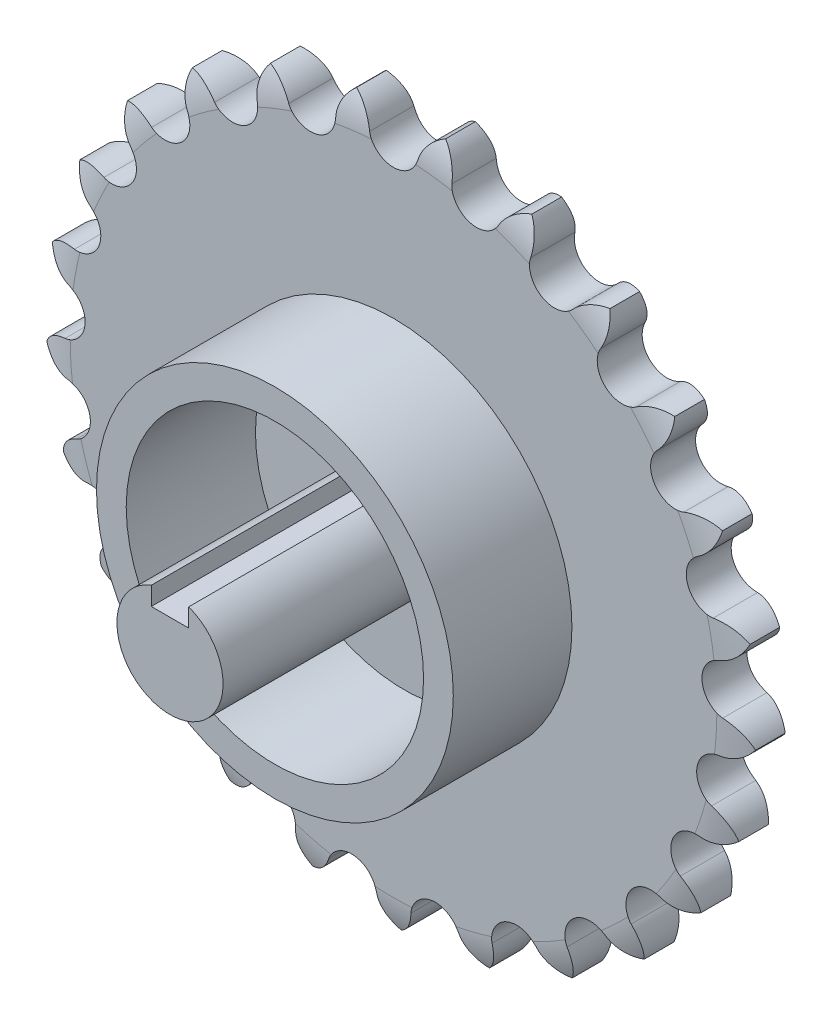
SolidWorks part; units mm, degrees
material "Acero aleado fundido"
ref_plane "Alzado" through (0, 0, 0) normal (0, 0, 1) x (1, 0, 0)
ref_plane "Planta" through (0, 0, 0) normal (0, 1, 0) x (1, 0, 0)
ref_plane "Vista lateral" through (0, 0, 0) normal (1, 0, 0) x (0, 0, -1)
sketch "Croquis1" plane through (0, 0, 0) normal (0, 0, 1) x (1, 0, 0)
  line L0 (0, 0) -> (0, 57) construction
  circle A0 centre (0, 0) radius 57 construction
  circle A1 centre (0, 0) radius 53.5 construction
  circle A2 centre (0, 0) radius 52 construction
  arc A5 (-3.8808, 52.5307) -> (3.8808, 52.5307) centre (0, 53.5) ccw
  arc A6 (7.3536, 56.5237) -> (3.8808, 52.5307) centre (9.537, 51.118) ccw
  arc A7 (15.1992, 49.7291) -> (15.3656, 51.246) centre (9.537, 51.118) ccw
  arc A8 (-7.3536, 56.5237) -> (-3.8808, 52.5307) centre (-9.537, 51.118) cw
  arc A9 (6.9343, 56.5766) -> (9.305, 51.8455) centre (3.4751, 51.8838) cw
  arc A10 (9.305, 51.8455) -> (16.8227, 49.9152) centre (13.3049, 51.8192) ccw
  arc A11 (21.1795, 52.9191) -> (16.8227, 49.9152) centre (21.9499, 47.1402) ccw
  arc A12 (20.7865, 53.0747) -> (21.9061, 47.9026) centre (16.2689, 49.3895) cw
  arc A13 (21.9061, 47.9026) -> (28.7076, 44.1634) centre (25.7738, 46.8824) ccw
  arc A14 (33.6745, 45.9894) -> (28.7076, 44.1634) centre (32.9836, 40.2005) ccw
  arc A15 (33.3325, 46.2379) -> (33.1308, 40.9498) centre (28.0405, 43.7919) cw
  arc A16 (33.1308, 40.9498) -> (38.7887, 35.6367) centre (36.6233, 38.9998) ccw
  arc A17 (44.0537, 36.1701) -> (38.7887, 35.6367) centre (41.9448, 30.7348) ccw
  arc A18 (43.7842, 36.4958) -> (42.2737, 31.424) centre (38.0501, 35.4427) cw
  arc A19 (42.2737, 31.424) -> (46.4326, 24.8707) centre (45.1715, 28.6667) ccw
  arc A20 (51.6648, 24.078) -> (46.4326, 24.8707) centre (48.2705, 19.338) ccw
  arc A21 (51.4848, 24.4605) -> (48.7604, 19.9237) centre (45.669, 24.8666) cw
  arc A22 (48.7604, 19.9237) -> (51.1589, 12.542) centre (50.8815, 16.5324) ccw
  arc A23 (56.0296, 10.4731) -> (51.1589, 12.542) centre (51.5632, 6.7261) ccw
  arc A24 (55.9504, 10.8883) -> (52.1834, 7.1716) centre (50.4183, 12.7279) cw
  arc A25 (52.1834, 7.1716) -> (52.6707, -0.5747) centre (53.3944, 3.3593) ccw
  arc A26 (56.8739, -3.79) -> (52.6707, -0.5747) centre (51.6159, -6.3085) ccw
  arc A27 (56.9004, -3.3681) -> (52.3274, -6.0312) centre (51.9996, -0.2105) cw
  arc A28 (52.3274, -6.0312) -> (50.8731, -13.6553) centre (52.5524, -10.0249) ccw
  arc A29 (54.1445, -17.8148) -> (50.8731, -13.6553) centre (48.4255, -18.9466) ccw
  arc A30 (54.2752, -17.4128) -> (49.1836, -18.855) centre (50.3136, -13.1356) cw
  arc A31 (49.1836, -18.855) -> (45.8788, -25.8779) centre (48.4082, -22.7792) ccw
  arc A32 (48.0131, -30.7204) -> (45.8788, -25.8779) centre (42.1922, -30.3943) ccw
  arc A33 (48.2396, -30.3635) -> (42.9493, -30.4941) centre (45.4662, -25.2354) cw
  arc A34 (42.9493, -30.4941) -> (38.0019, -36.4745) centre (41.2225, -34.1022) ccw
  arc A35 (38.8649, -41.6956) -> (38.0019, -36.4745) centre (33.3079, -39.9322) ccw
  arc A36 (39.173, -41.4063) -> (34.0164, -40.2172) centre (37.762, -35.7496) cw
  arc A37 (34.0164, -40.2172) -> (27.7372, -44.7793) centre (31.4465, -43.2824) ccw
  arc A38 (27.2746, -50.051) -> (27.7372, -44.7793) centre (22.3308, -46.961) ccw
  arc A39 (27.645, -49.8473) -> (22.9461, -47.4132) centre (27.6851, -44.0175) cw
  arc A40 (22.9461, -47.4132) -> (15.7296, -50.2704) centre (19.6947, -49.743) ccw
  arc A41 (13.9705, -55.2614) -> (15.7296, -50.2704) centre (9.9505, -51.0391) ccw
  arc A42 (14.3799, -55.1563) -> (10.434, -51.6301) centre (15.8686, -49.5196) cw
  arc A43 (10.434, -51.6301) -> (2.7337, -52.6029) centre (6.7053, -53.0781) ccw
  arc A44 (-0.2113, -56.9996) -> (2.7337, -52.6029) centre (-3.055, -51.9102) ccw
  arc A45 (0.2113, -56.9996) -> (-2.7337, -52.6029) centre (3.055, -51.9102) cw
  arc A46 (-2.7337, -52.6029) -> (-10.434, -51.6301) centre (-6.7053, -53.0781) ccw
  arc A47 (-14.3799, -55.1563) -> (-10.434, -51.6301) centre (-15.8686, -49.5196) ccw
  arc A48 (-13.9705, -55.2614) -> (-15.7296, -50.2704) centre (-9.9505, -51.0391) cw
  arc A49 (-15.7296, -50.2704) -> (-22.9461, -47.4132) centre (-19.6947, -49.743) ccw
  arc A50 (-27.645, -49.8473) -> (-22.9461, -47.4132) centre (-27.6851, -44.0175) ccw
  arc A51 (-27.2746, -50.051) -> (-27.7372, -44.7793) centre (-22.3308, -46.961) cw
  arc A52 (-27.7372, -44.7793) -> (-34.0164, -40.2172) centre (-31.4465, -43.2824) ccw
  arc A53 (-39.173, -41.4063) -> (-34.0164, -40.2172) centre (-37.762, -35.7496) ccw
  arc A54 (-38.8649, -41.6956) -> (-38.0019, -36.4745) centre (-33.3079, -39.9322) cw
  arc A55 (-38.0019, -36.4745) -> (-42.9493, -30.4941) centre (-41.2225, -34.1022) ccw
  arc A56 (-48.2396, -30.3635) -> (-42.9493, -30.4941) centre (-45.4662, -25.2354) ccw
  arc A57 (-48.0131, -30.7204) -> (-45.8788, -25.8779) centre (-42.1922, -30.3943) cw
  arc A58 (-45.8788, -25.8779) -> (-49.1836, -18.855) centre (-48.4082, -22.7792) ccw
  arc A59 (-54.2752, -17.4128) -> (-49.1836, -18.855) centre (-50.3136, -13.1356) ccw
  arc A60 (-54.1445, -17.8148) -> (-50.8731, -13.6553) centre (-48.4255, -18.9466) cw
  arc A61 (-50.8731, -13.6553) -> (-52.3274, -6.0312) centre (-52.5524, -10.0249) ccw
  arc A62 (-56.9004, -3.3681) -> (-52.3274, -6.0312) centre (-51.9996, -0.2105) ccw
  arc A63 (-56.8739, -3.79) -> (-52.6707, -0.5747) centre (-51.6159, -6.3085) cw
  arc A64 (-52.6707, -0.5747) -> (-52.1834, 7.1716) centre (-53.3944, 3.3593) ccw
  arc A65 (-55.9504, 10.8883) -> (-52.1834, 7.1716) centre (-50.4183, 12.7279) ccw
  arc A66 (-56.0296, 10.4731) -> (-51.1589, 12.542) centre (-51.5632, 6.7261) cw
  arc A67 (-51.1589, 12.542) -> (-48.7604, 19.9237) centre (-50.8815, 16.5324) ccw
  arc A68 (-51.4848, 24.4605) -> (-48.7604, 19.9237) centre (-45.669, 24.8666) ccw
  arc A69 (-51.6648, 24.078) -> (-46.4326, 24.8707) centre (-48.2705, 19.338) cw
  arc A70 (-46.4326, 24.8707) -> (-42.2737, 31.424) centre (-45.1715, 28.6667) ccw
  arc A71 (-43.7842, 36.4958) -> (-42.2737, 31.424) centre (-38.0501, 35.4427) ccw
  arc A72 (-44.0537, 36.1701) -> (-38.7887, 35.6367) centre (-41.9448, 30.7348) cw
  arc A73 (-38.7887, 35.6367) -> (-33.1308, 40.9498) centre (-36.6233, 38.9998) ccw
  arc A74 (-33.3325, 46.2379) -> (-33.1308, 40.9498) centre (-28.0405, 43.7919) ccw
  arc A75 (-33.6745, 45.9894) -> (-28.7076, 44.1634) centre (-32.9836, 40.2005) cw
  arc A76 (-28.7076, 44.1634) -> (-21.9061, 47.9026) centre (-25.7738, 46.8824) ccw
  arc A77 (-20.7865, 53.0747) -> (-21.9061, 47.9026) centre (-16.2689, 49.3895) ccw
  arc A78 (-21.1795, 52.9191) -> (-16.8227, 49.9152) centre (-21.9499, 47.1402) cw
  arc A79 (-16.8227, 49.9152) -> (-9.305, 51.8455) centre (-13.3049, 51.8192) ccw
  arc A80 (-6.9343, 56.5766) -> (-9.305, 51.8455) centre (-3.4751, 51.8838) ccw
  circle A81 centre (0, 0) radius 19
  point P186 (0, 0)
  dimension "D1" = 114
  dimension "D2" = 107
  dimension "D3" = 104
  dimension "D4" = 8
  dimension "D5" = 11.66
  dimension "D7" = 38
  dimension "D6" = 25
extrude "Saliente-Extruir1" add sketch "Croquis1" along normal mid plane 7.2 contours A8 A80 A79 A78 A77 A76 A75 A74 A73 A72 A71 A70 A69 A68 A67 A66 A65 A64 A63 A62 A61 A60 A59 A58 A57 A56 A55 A54 A53 A52 A51 A50 A49 A48 A47 A46 A45 A44 A43 A42 A41 A40 A39 A38 A37 A36 A35 A34 A33 A32 A31
sketch "Croquis2" plane through (0, 0, 3.6) normal (0, 0, 1) x (1, 0, 0)
  circle A0 centre (0, 0) radius 28.575
  circle A1 centre (0, 0) radius 19 construction
  circle A2 centre (0, 0) radius 19
  dimension "D1" = 57.15
extrude "Saliente-Extruir2" add sketch "Croquis2" along normal blind 19
sketch "Croquis3" plane through (0, 0, 22.6) normal (0, 0, 1) x (1, 0, 0)
  line L0 (0, 0) -> (0, 19) construction
  line L2 (-4.75, 21.4) -> (4.75, 21.4)
  line L3 (-4.75, 21.4) -> (-4.75, 16.6)
  line L4 (-4.75, 16.6) -> (4.75, 16.6)
  line L5 (4.75, 21.4) -> (4.75, 16.6)
  line L6 (-4.75, 21.4) -> (4.75, 16.6) construction
  line L7 (-4.75, 16.6) -> (4.75, 21.4) construction
  circle A1 centre (0, 0) radius 19 construction
  dimension "D1" = 9.5
  dimension "D2" = 4.8
extrude "Cortar-Extruir1" cut sketch "Croquis3" against normal through all
sketch "Croquis4" plane through (0, 0, 0) normal (1, 0, 0) x (0, 0, -1)
  line L0 (0, 56.4271) -> (0, 47.0486) construction
  line L1 (-3.6, 56.4271) -> (3.6, 56.4271) construction
  line L2 (-2.1, 58.8113) -> (-2.1, 48.3808) construction
  line L3 (-3.6, 56.4271) -> (-3.6, 51.8455) construction
  line L4 (-2.1, 57.4271) -> (-9.3502, 57.4271)
  line L5 (-9.3502, 57.4271) -> (-9.3502, 51.0771)
  line L6 (-9.3502, 51.0771) -> (-3.6, 51.0771)
  line L7 (-3.6, 52.8816) -> (-3.6, 47.9026) construction
  line L8 (9.3502, 51.0771) -> (3.6, 51.0771)
  line L9 (9.3502, 57.4271) -> (9.3502, 51.0771)
  line L10 (2.1, 57.4271) -> (9.3502, 57.4271)
  arc A0 (-2.1, 57.4271) -> (-3.6, 51.0771) centre (9.0951, 51.4305) ccw
  arc A1 (2.1, 57.4271) -> (3.6, 51.0771) centre (-9.0951, 51.4305) cw
  dimension "D2" = 12.7
  dimension "D1" = 1.5
  dimension "D3" = 1
  dimension "D4" = 6.35
ref_axis "Eje1" through (0, 0, 81.5759) along (0, 0, -1)
revolve "Cortar-Revolución1" cut sketch "Croquis4" angle 360 about axis through (0, 0, 81.5759) along (0, 0, -1)
sketch "Croquis5" plane through (0, 0, 22.6) normal (0, 0, 1) x (1, 0, 0)
  line L0 (-4.75, 18.3967) -> (-4.75, 21.4)
  line L1 (-4.75, 21.4) -> (4.75, 21.4)
  line L2 (4.75, 21.4) -> (4.75, 18.3967)
  line L3 (4.75, 18.3967) -> (4.75, 21.4) construction
  arc A0 (-4.75, 18.3967) -> (4.75, 18.3967) centre (0, 0) ccw
extrude "Saliente-Extruir4" add sketch "Croquis5" against normal blind 70.2 and the other way blind 4
sketch "Croquis6" plane through (0, 0, -47.6) normal (0, 0, -1) x (-1, 0, 0)
  line L0 (-3, 5.003) -> (-3, 7.953)
  line L1 (-3, 5.003) -> (3, 5.003)
  line L2 (3, 5.003) -> (3, 7.953)
  arc A0 (-3, 7.953) -> (3, 7.953) centre (0, 0) ccw
  circle A1 centre (0, 0) radius 10.5
  dimension "D1" = 17
  dimension "D2" = 21
  dimension "D3" = 6
  dimension "D4" = 2.95
  dimension "D5" = 2.95
extrude "Cortar-Extruir2" cut sketch "Croquis6" against normal blind 128 contours A0 L2 L1 L0
sketch "Croquis8" plane through (0, 0, -47.6) normal (0, 0, -1) x (-1, 0, 0)
  line L0 (-3, 5.003) -> (3, 5.003)
  line L1 (3, 5.003) -> (3, 7.953)
  line L2 (-3, 5.003) -> (-3, 7.953)
  line L3 (-4.75, 18.3967) -> (-4.75, 21.4)
  line L4 (-4.75, 21.4) -> (4.75, 21.4)
  line L5 (4.75, 21.4) -> (4.75, 18.3967)
  arc A0 (-3, 7.953) -> (3, 7.953) centre (0, 0) ccw
  arc A1 (-4.75, 18.3967) -> (4.75, 18.3967) centre (0, 0) ccw
extrude "Cortar-Extruir3" cut sketch "Croquis8" against normal blind 44 contours A1 L5 L4 L3
sketch "Croquis9" plane through (0, 0, 26.6) normal (0, 0, 1) x (1, 0, 0)
  circle A1 centre (0, 0) radius 28.4343
extrude "Cortar-Extruir4" cut sketch "Croquis9" against normal blind 4
sketch "Croquis10" plane through (0, 0, 22.6) normal (0, 0, 1) x (1, 0, 0)
  circle A0 centre (0, 0) radius 23.8125
  dimension "D1" = 47.625
extrude "Cortar-Extruir5" cut sketch "Croquis10" against normal blind 20.7
sketch "Croquis11" plane through (0, 0, -3.6) normal (0, 0, -1) x (-1, 0, 0)
  line L0 (-3, 7.953) -> (-3, 5.003) construction
  line L1 (3, 5.003) -> (-3, 5.003) construction
  line L2 (-3, 7.953) -> (-3, 5.003)
  line L3 (3, 5.003) -> (-3, 5.003)
  line L4 (3, 7.953) -> (3, 5.003) construction
  line L5 (3, 7.953) -> (3, 5.003)
  arc A0 (-3, 7.953) -> (3, 7.953) centre (0, 0) ccw construction
  arc A1 (-3, 7.953) -> (3, 7.953) centre (0, 0) ccw
extrude "Saliente-Extruir5" add sketch "Croquis11" against normal blind 43
